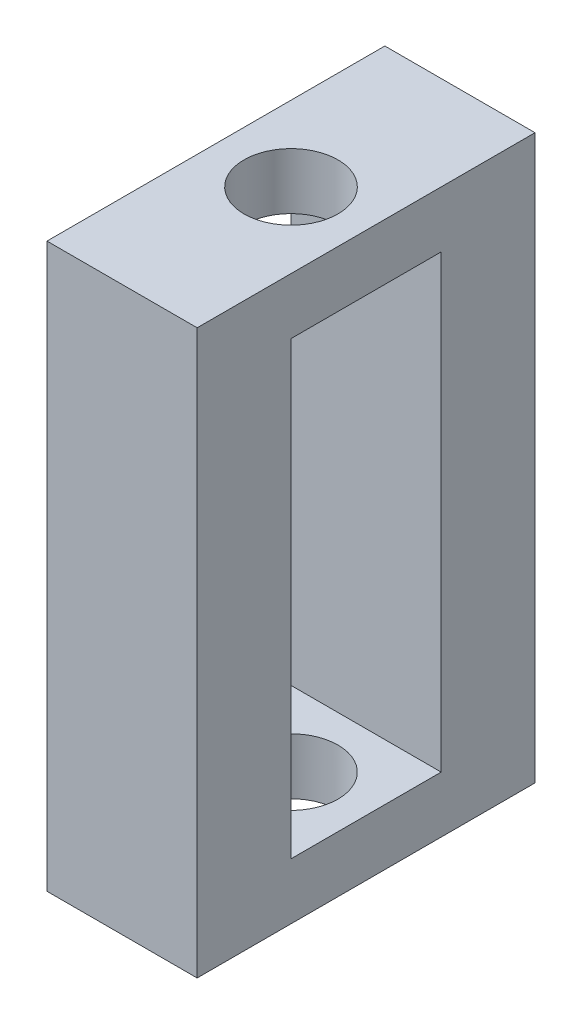
SolidWorks part; units mm, degrees
ref_plane "Front Plane" through (0, 0, 0) normal (0, 0, 1) x (1, 0, 0)
ref_plane "Top Plane" through (0, 0, 0) normal (0, 1, 0) x (1, 0, 0)
ref_plane "Right Plane" through (0, 0, 0) normal (1, 0, 0) x (0, 0, -1)
sketch "Sketch2" plane through (0, 0, 0) normal (0, 1, 0) x (1, 0, 0)
  line L1 (0, 0) -> (8, 0)
  line L2 (0, 0) -> (0, 18)
  line L3 (0, 18) -> (8, 18)
  line L4 (8, 0) -> (8, 18)
  dimension "D1" = 18
  dimension "D2" = 8
extrude "Boss-Extrude1" add sketch "Sketch2" along normal blind 30 contours L2 L3 L4 L1
sketch "Sketch3" plane through (0, 30, 0) normal (0, 1, 0) x (1, 0, 0)
  line L0 (0, 0) -> (8, 0) construction
  line L1 (0, 0) -> (0, 18) construction
  circle A0 centre (4, 9) radius 2.5
  point P2 (0, 0)
  point P5 (4, 0)
  point P8 (0, 9)
  dimension "D1" = 5
extrude "Cut-Extrude1" cut sketch "Sketch3" against normal blind 30
ref_plane "Plane1" through (8, 30, 0) normal (0, 0, -1) x (-1, 0, 0)
sketch "Sketch5" plane through (8, 0, 0) normal (1, 0, 0) x (0, 0, -1)
  line L0 (0, 30) -> (18, 30) construction
  line L1 (5, 27) -> (13, 27)
  line L2 (5, 27) -> (5, 3)
  line L3 (5, 3) -> (13, 3)
  line L4 (13, 27) -> (13, 3)
  line L5 (0, 0) -> (18, 0) construction
  line L6 (0, 30) -> (0, 0) construction
  point P6 (9, 30)
  dimension "D1" = 8
  dimension "D2" = 3
  dimension "D3" = 3
  dimension "D4" = 5
extrude "Cut-Extrude2" cut sketch "Sketch5" against normal blind 30
